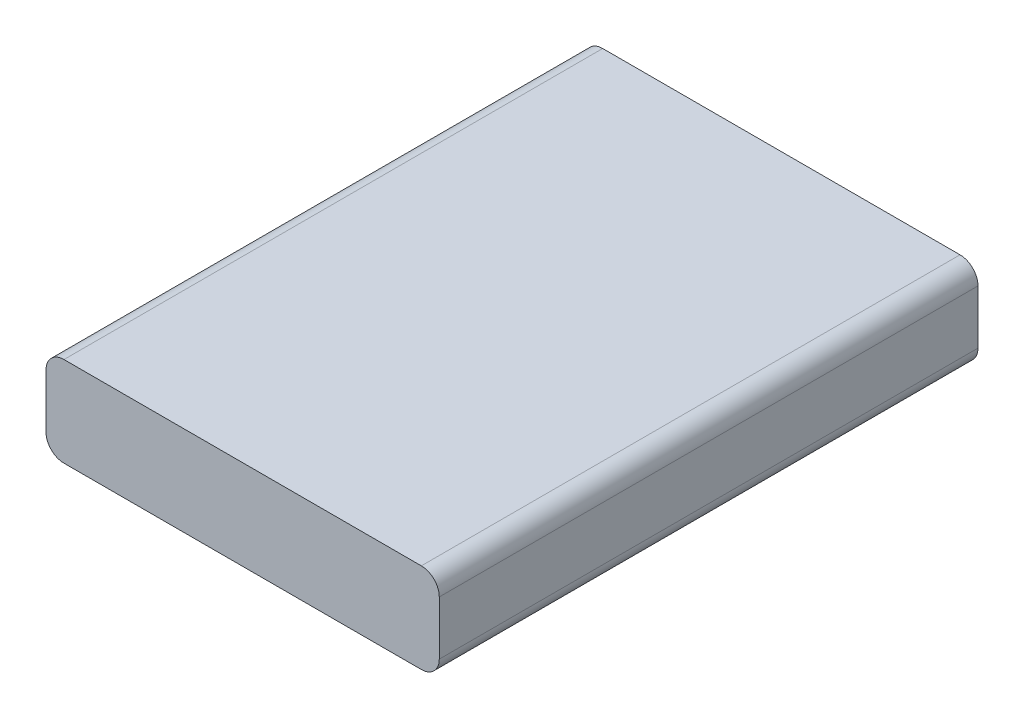
SolidWorks part; units mm, degrees
material "黄铜"
ref_plane "前视基准面" through (0, 0, 0) normal (0, 0, 1) x (1, 0, 0)
ref_plane "上视基准面" through (0, 0, 0) normal (0, 1, 0) x (1, 0, 0)
ref_plane "右视基准面" through (0, 0, 0) normal (1, 0, 0) x (0, 0, -1)
other "Configuration Table"
sketch "草图1" plane through (0, 0, 0) normal (0, 0, 1) x (1, 0, 0)
  line L1 (-10.95, 2.5) -> (10.95, 2.5)
  line L2 (-10.95, 2.5) -> (-10.95, -2.5)
  line L3 (-10.95, -2.5) -> (10.95, -2.5)
  line L4 (10.95, 2.5) -> (10.95, -2.5)
  line L5 (-10.95, 2.5) -> (10.95, -2.5) construction
  line L6 (-10.95, -2.5) -> (10.95, 2.5) construction
  point P6 (0, 0)
  dimension "D3" = 21.9
  dimension "D4" = 5
extrude "凸台-拉伸1" add sketch "草图1" along normal blind 30
fillet "圆角2" radius 1 4 edges at (10.95, -2.5, 15) (-10.95, -2.5, 15) (-10.95, 2.5, 15) (10.95, 2.5, 15)
sketch "草图3" plane through (0, 0, 0) normal (0, 0, -1) x (-1, 0, 0)
  line L1 (0, 0) -> (0, 10.9525) construction
  point P0 (-5, 0)
  point P2 (5, 0)
  dimension "D1" = 10
hole_wizard "M2.5 螺纹孔1" positions "草图3" profile "草图4" tap size "M2.5" standard "GB"
sketch "草图4" plane through (5, 0, 0) normal (1, 0, 0) x (0, 1, 0)
  line L0 (0, 0) -> (0, 7.8659)
  line L1 (0, 7.8659) -> (1.025, 7.25)
  line L2 (1.025, 7.25) -> (1.025, 0)
  line L5 (1.025, 0) -> (0, 0)
  line L10 (0, 7.8659) -> (-1.025, 7.25) construction
  line L11 (0, -6.35) -> (0, 107.95) construction
  dimension "螺纹孔钻头直径" = 2.05
  dimension "螺纹孔钻头深度" = 7.25
  dimension "导头角度" = 118
cosmetic thread "孔螺蚊线1" parameters "D1"=5, "D2"=3.05
cosmetic thread "孔螺蚊线2" parameters "D1"=5, "D2"=3.05
